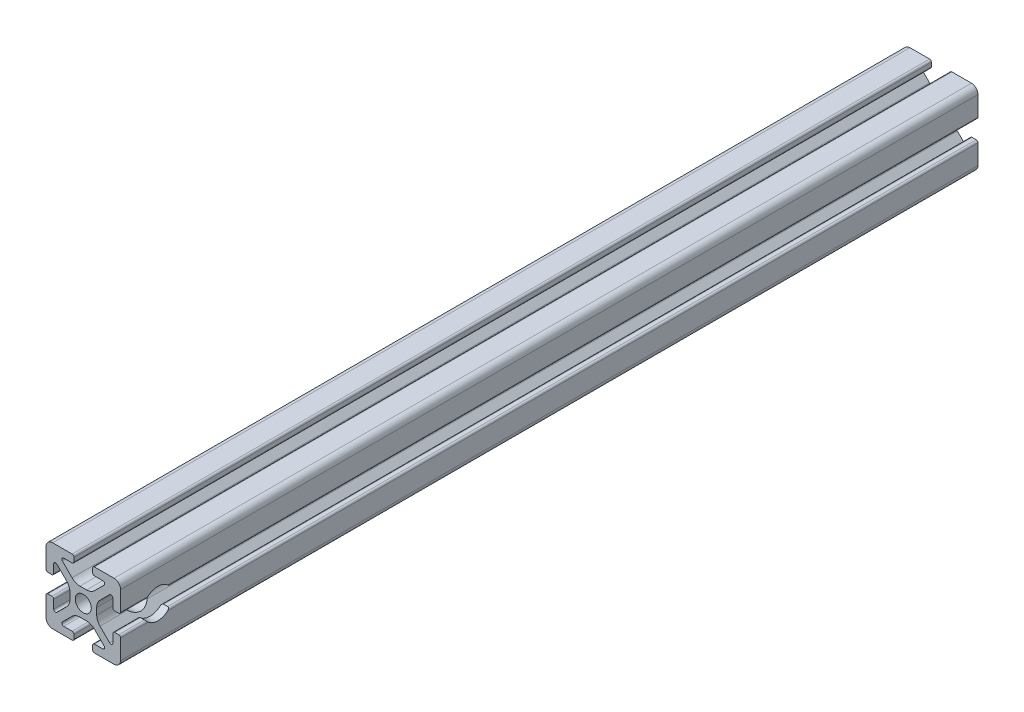
SolidWorks part; units mm, degrees
material "6063-T6"
ref_plane "Front Plane" through (0, 0, 0) normal (0, 0, 1) x (1, 0, 0)
ref_plane "Top Plane" through (0, 0, 0) normal (0, 1, 0) x (1, 0, 0)
ref_plane "Right Plane" through (0, 0, 0) normal (1, 0, 0) x (0, 0, -1)
sketch "Sketch2" plane through (0, 0, 0) normal (0, 0, 1) x (1, 0, 0)
  line L0 (0, 10) -> (0, -10) construction
  line L1 (-10, 0) -> (10, 0) construction
  line L2 (2.5, -10) -> (10, -10)
  line L3 (10, -10) -> (10, -2.5)
  line L4 (2.5, -10) -> (2.5, -7.9246)
  line L5 (2.5, -7.9246) -> (6.4571, -7.9246)
  line L6 (6.4571, -7.9246) -> (2.1325, -3.6)
  line L7 (0, 0) -> (10, -10) construction
  line L8 (10, -2.5) -> (7.9246, -2.5)
  line L9 (7.9246, -2.5) -> (7.9246, -6.4571)
  line L10 (7.9246, -6.4571) -> (3.6, -2.1325)
  line L11 (5.7623, -4.2948) -> (4.2948, -5.7623) construction
  circle A0 centre (0, 0) radius 2.15
  arc A1 (5.25, -7.9246) -> (5.6036, -7.0711) centre (5.25, -7.4246) ccw construction
  point P8 (0, -3.6)
  point P16 (5.0286, -5.0286)
  dimension "Center Hole Diameter" = 4.3
  dimension "D3" = 0.5
  dimension "Rail Height" = 20
  dimension "Rail Width" = 20
  dimension "T-Slot Width" = 5
  dimension "Slot Depth" = 6.4
  dimension "Slot Inner Width" = 11.5
sketch "Sketch3" plane through (0, 0, 0) normal (1, 0, 0) x (0, 0, -1)
  line L0 (-115, -10) -> (115, -10) construction
  line L1 (-89.6, 0) -> (89.6, 0) construction
  line L2 (0, 10) -> (0, -10) construction
  line L3 (0, 10) -> (0, -10) construction
  point P6 (-89.6, 0)
  point P8 (89.6, 0)
  dimension "Length" = 230
  dimension "D1" = 25.4
sketch "Sketch4" plane through (0, 0, 0) normal (0, 0, 1) x (1, 0, 0)
  line L0 (3, -10) -> (8.25, -10)
  line L1 (2.5, -10) -> (10, -10) construction
  line L2 (2.5, -10) -> (2.5, -7.9246) construction
  line L3 (2.5, -7.9246) -> (6.4571, -7.9246) construction
  line L4 (2.5, -8.4246) -> (2.5, -9.5)
  line L5 (3, -7.9246) -> (5.25, -7.9246)
  line L6 (0, -3.6) -> (0.8898, -3.6)
  line L7 (6.4571, -7.9246) -> (2.1325, -3.6) construction
  line L8 (3.0112, -4.4787) -> (5.6036, -7.0711)
  line L9 (10, -10) -> (10, -2.5) construction
  line L10 (7.9246, -6.4571) -> (3.6, -2.1325) construction
  line L11 (7.9246, -2.5) -> (7.9246, -6.4571) construction
  line L12 (7.9246, -5.25) -> (7.9246, -3)
  line L13 (10, -2.5) -> (7.9246, -2.5) construction
  line L14 (8.4246, -2.5) -> (9.5, -2.5)
  line L15 (10, -3) -> (10, -8.25)
  line L16 (7.0711, -5.6036) -> (4.4787, -3.0112)
  line L17 (3.6, 0) -> (3.6, -0.8898)
  line L18 (-10, 0) -> (10, 0) construction
  line L19 (0, -3.6) -> (0, -2.15)
  line L20 (0, 10) -> (0, -10) construction
  line L21 (3.6, 0) -> (2.15, 0)
  arc A0 (2.5, -9.5) -> (3, -10) centre (3, -9.5) ccw
  arc A1 (5.25, -7.9246) -> (5.6036, -7.0711) centre (5.25, -7.4246) ccw construction
  arc A2 (2.5, -8.4246) -> (3, -7.9246) centre (3, -8.4246) cw
  arc A3 (5.25, -7.9246) -> (5.6036, -7.0711) centre (5.25, -7.4246) ccw
  arc A4 (0.8898, -3.6) -> (3.0112, -4.4787) centre (0.8898, -6.6) cw
  arc A5 (8.25, -10) -> (10, -8.25) centre (8.25, -8.25) ccw
  arc A6 (7.0711, -5.6036) -> (7.9246, -5.25) centre (7.4246, -5.25) ccw
  arc A7 (7.9246, -3) -> (8.4246, -2.5) centre (8.4246, -3) cw
  arc A8 (9.5, -2.5) -> (10, -3) centre (9.5, -3) cw
  arc A9 (4.4787, -3.0112) -> (3.6, -0.8898) centre (6.6, -0.8898) cw
  circle A10 centre (0, 0) radius 2.15 construction
  arc A11 (0, -2.15) -> (2.15, 0) centre (0, 0) ccw
  dimension "D1" = 1.75
  dimension "D2" = 3
extrude "Boss-Extrude1" add sketch "Sketch4" along normal mid plane 230
mirror "Mirror1" about plane through (0, 0, 0) normal (1, 0, 0) of bodies 134
mirror "Mirror2" about plane through (0, 0, 0) normal (0, 1, 0) of bodies 135
sketch "Sketch5" plane through (-10, 0, 0) normal (-1, 0, 0) x (0, 0, 1)
  line L0 (115, -0.8898) -> (115, 0.8898) construction
  circle A0 centre (105, 0) radius 4
  dimension "D1" = 10
extrude "Cut-Extrude1" cut sketch "Sketch5" against normal blind 20
equation "\"D3@Sketch2\"=\"T-Slot Width@Sketch2\"*0.1"
equation "\"D1@Sketch4\"=\"D3@Sketch2\"*3.5"
equation "\"D2@Sketch4\"=\"D3@Sketch2\"*6"
equation "\"D1@Boss-Extrude1\"=\"Length@Sketch3\""
